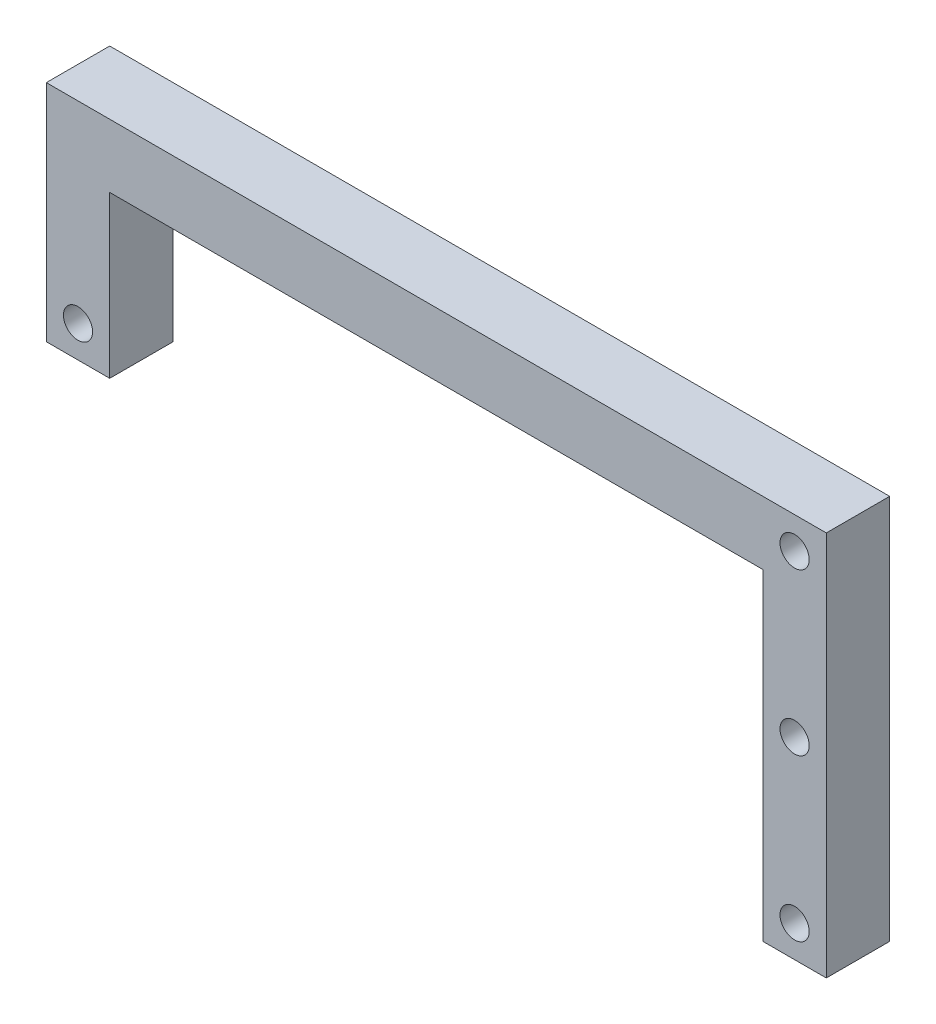
SolidWorks part; units mm, degrees
ref_plane "Front Plane" through (0, 0, 0) normal (0, 0, 1) x (1, 0, 0)
ref_plane "Top Plane" through (0, 0, 0) normal (0, 1, 0) x (1, 0, 0)
ref_plane "Right Plane" through (0, 0, 0) normal (1, 0, 0) x (0, 0, -1)
sketch "Sketch1" plane through (0, 0, 0) normal (0, 0, 1) x (1, 0, 0)
  line L0 (108.03, -30.4) -> (118.03, -30.4)
  line L1 (118.03, -30.4) -> (118.03, 30.4)
  line L2 (118.03, 30.4) -> (-5, 30.4)
  line L3 (-5, 30.4) -> (-5, -5)
  line L4 (-5, -5) -> (5, -5)
  line L5 (5, -5) -> (5, 20.4)
  line L6 (5, 20.4) -> (108.03, 20.4)
  line L7 (108.03, 20.4) -> (108.03, -30.4)
  line L8 (-5, 25.4) -> (118.03, 25.4) construction
  circle A0 centre (0, 0) radius 2.3
  circle A1 centre (113.03, 0) radius 2.3
  circle A2 centre (113.03, -25.4) radius 2.3
  circle A3 centre (113.03, 25.4) radius 2.3
  point P9 (0, -5)
  point P16 (113.03, -30.4)
  point P21 (0, 0)
  dimension "D3" = 4.6
  dimension "D1" = 113.03
  dimension "D2" = 25.4
  dimension "D4" = 5
  dimension "D5" = 10
  dimension "D6" = 10
  dimension "D7" = 10
  dimension "D8" = 5
  dimension "D9" = 5
  dimension "D10" = 25.4
extrude "Boss-Extrude1" add sketch "Sketch1" along normal blind 10
